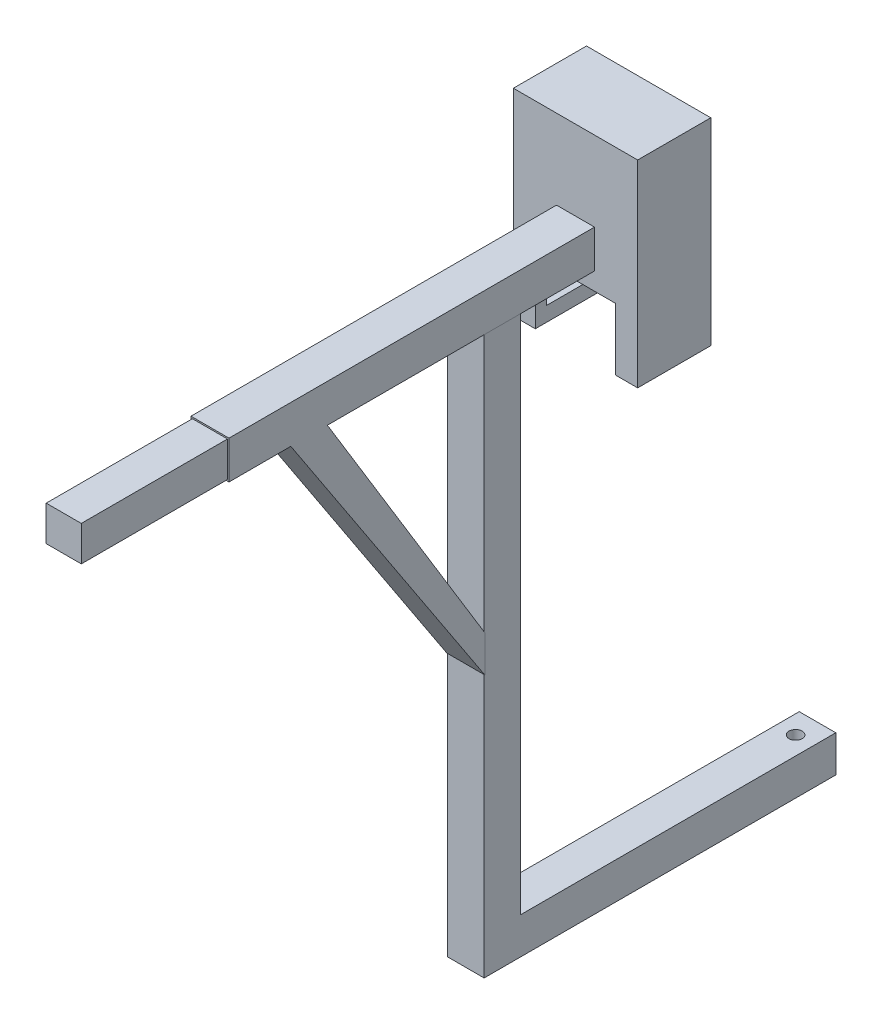
SolidWorks part; units mm, degrees
ref_plane "Front Plane" through (0, 0, 0) normal (0, 0, 1) x (1, 0, 0)
ref_plane "Top Plane" through (0, 0, 0) normal (0, 1, 0) x (1, 0, 0)
ref_plane "Right Plane" through (0, 0, 0) normal (1, 0, 0) x (0, 0, -1)
sketch "Sketch1" plane through (0, 0, 0) normal (0, 0, 1) x (1, 0, 0)
  line L1 (0, 0) -> (4.8, 0)
  line L2 (0, 0) -> (0, -4.8)
  line L3 (0, -4.8) -> (4.8, -4.8)
  line L4 (4.8, 0) -> (4.8, -4.8)
  dimension "D1" = 4.8
  dimension "D2" = 4.8
extrude "Boss-Extrude1" add sketch "Sketch1" along normal blind 20
sketch "Sketch2" plane through (0, 0, 0) normal (0, 0, -1) x (-1, 0, 0)
  line L0 (0, 0) -> (0, -4.8) construction
  line L1 (-5, 0.2) -> (0.2, 0.2)
  line L2 (-5, 0.2) -> (-5, -5)
  line L3 (-5, -5) -> (0.2, -5)
  line L4 (0.2, 0.2) -> (0.2, -5)
  line L5 (-5, 0.2) -> (0.2, -5) construction
  line L6 (-5, -5) -> (0.2, 0.2) construction
  line L7 (-4.8, 0) -> (0, 0) construction
  point P0 (-2.4, -2.4)
  dimension "D1" = 5.2
  dimension "D2" = 5.2
  dimension "D3" = 2.4
  dimension "D4" = 2.4
extrude "Boss-Extrude2" add sketch "Sketch2" along normal blind 50
sketch "Sketch3" plane through (0, 0, -50) normal (0, 0, -1) x (-1, 0, 0)
  line L0 (-5, -5) -> (0.2, -5) construction
  line L1 (-10.9, 11.1) -> (6.1, 11.1)
  line L2 (-10.9, 11.1) -> (-10.9, -15.9)
  line L3 (-10.9, -15.9) -> (6.1, -15.9)
  line L4 (6.1, 11.1) -> (6.1, -15.9)
  line L5 (-10.9, 11.1) -> (6.1, -15.9) construction
  line L6 (-10.9, -15.9) -> (6.1, 11.1) construction
  line L7 (0.2, -5) -> (0.2, 0.2) construction
  point P0 (-2.4, -2.4)
  dimension "D1" = 27
  dimension "D2" = 17
  dimension "D3" = 2.6
  dimension "D4" = 2.6
extrude "Boss-Extrude3" add sketch "Sketch3" along normal blind 10
sketch "Sketch4" plane through (0, 0, -60) normal (0, 0, -1) x (-1, 0, 0)
  line L0 (6.1, 11.1) -> (-10.9, 11.1) construction
  line L1 (4.1, 9.1) -> (-8.9, 9.1)
  line L2 (4.1, 9.1) -> (4.1, -13.9)
  line L3 (4.1, -13.9) -> (-8.9, -13.9)
  line L4 (-8.9, 9.1) -> (-8.9, -13.9)
  line L5 (4.1, 9.1) -> (-8.9, -13.9) construction
  line L6 (4.1, -13.9) -> (-8.9, 9.1) construction
  line L7 (6.1, -15.9) -> (6.1, 11.1) construction
  point P0 (-2.4, -2.4)
  dimension "D1" = 13
  dimension "D2" = 23
  dimension "D3" = 13.5
  dimension "D4" = 8.5
extrude "Cut-Extrude1" cut sketch "Sketch4" against normal blind 8.5
sketch "Sketch5" plane through (0, -15.9, 0) normal (0, -1, 0) x (1, 0, 0)
  line L0 (10.9, -50) -> (-6.1, -50) construction
  line L1 (-3.1, -50) -> (7.9, -50)
  line L2 (-3.1, -50) -> (-3.1, -58.5)
  line L3 (-3.1, -58.5) -> (7.9, -58.5)
  line L4 (7.9, -50) -> (7.9, -58.5)
  line L5 (10.9, -60) -> (-6.1, -60) construction
  line L6 (10.9, -60) -> (10.9, -50) construction
  line L7 (-6.1, -60) -> (-6.1, -50) construction
  point P10 (10.9, -55)
  dimension "D1" = 1.5
  dimension "D2" = 3
  dimension "D3" = 3
extrude "Cut-Extrude2" cut sketch "Sketch5" against normal blind 8.5
sketch "Sketch6" plane through (0, 0.2, 0) normal (0, 1, 0) x (1, 0, 0)
  line L0 (5, 50) -> (5, 0) construction
  line L1 (-0.1, 40) -> (4.9, 40)
  line L2 (-0.1, 40) -> (-0.1, 35)
  line L3 (-0.1, 35) -> (4.9, 35)
  line L4 (4.9, 40) -> (4.9, 35)
  line L5 (-0.1, 40) -> (4.9, 35) construction
  line L6 (-0.1, 35) -> (4.9, 40) construction
  line L7 (-0.2, 50) -> (5, 50) construction
  point P0 (2.4, 37.5)
  dimension "D1" = 5
  dimension "D2" = 5
  dimension "D3" = 2.6
  dimension "D4" = 10
extrude "Boss-Extrude4" add sketch "Sketch6" against normal blind 81.5
sketch "Sketch7" plane through (0, 0, -40) normal (0, 0, -1) x (-1, 0, 0)
  line L0 (0.1, -81.3) -> (0.1, -5) construction
  line L1 (-4.9, -81.3) -> (0.1, -81.3)
  line L2 (-4.9, -81.3) -> (-4.9, -76.3)
  line L3 (-4.9, -76.3) -> (0.1, -76.3)
  line L4 (0.1, -81.3) -> (0.1, -76.3)
  dimension "D1" = 5
  dimension "D2" = 5
extrude "Boss-Extrude5" add sketch "Sketch7" along normal blind 43.1
sketch "Sketch9" plane through (0, -81.3, 0) normal (0, -1, 0) x (1, 0, 0)
  line L0 (-0.1, -35) -> (4.9, -35) construction
  line L1 (4.9, -35) -> (4.9, -83.1) construction
  line L2 (-0.1, -83.1) -> (-0.1, -35) construction
  circle A0 centre (2.4, -80.1) radius 0.9
  dimension "D1" = 45.1
  dimension "D2" = 1.8
  dimension "D3" = 2.5
  dimension "D4" = 2.5
extrude "Cut-Extrude4" cut sketch "Sketch9" against normal through all
sketch "Sketch10" plane through (0, 0, -35) normal (0, 0, 1) x (1, 0, 0)
  line L0 (-0.1, -81.3) -> (-0.1, -5) construction
  line L1 (-0.1, -45.3599) -> (4.9, -45.3599)
  line L2 (-0.1, -45.3599) -> (-0.1, -40.3599)
  line L3 (-0.1, -40.3599) -> (4.9, -40.3599)
  line L4 (4.9, -45.3599) -> (4.9, -40.3599)
  line L5 (4.9, -81.3) -> (4.9, -5) construction
  dimension "D1" = 5
  dimension "D2" = 5
sketch "Sketch11" plane through (0, -5, 0) normal (0, -1, 0) x (1, 0, 0)
  line L0 (-0.2, -50) -> (-0.2, 0) construction
  line L1 (-0.2, -13.4558) -> (5, -13.4558)
  line L2 (-0.2, -13.4558) -> (-0.2, -8.4558)
  line L3 (-0.2, -8.4558) -> (5, -8.4558)
  line L4 (5, -13.4558) -> (5, -8.4558)
  line L5 (5, -50) -> (5, 0) construction
  dimension "D1" = 5
  dimension "D2" = 5.2
sketch "Sketch12" plane through (5, 0, 0) normal (1, 0, 0) x (0, 0, -1)
  line L0 (13.4558, -5) -> (35, -40.3599)
  line L1 (13.4558, -5) -> (8.4558, -5) construction
  line L2 (50, -5) -> (0, -5) construction
  line L3 (35, -45.3599) -> (35, -40.3599) construction
  line L4 (35, -45.3599) -> (35, -40.3599) construction
  line L5 (8.4558, -5) -> (35, -45.3599)
  line L6 (8.4558, -5) -> (13.4558, -5)
  line L7 (35, -40.3599) -> (35, -45.3599)
extrude "Boss-Extrude6" add sketch "Sketch12" against normal blind 5.2
